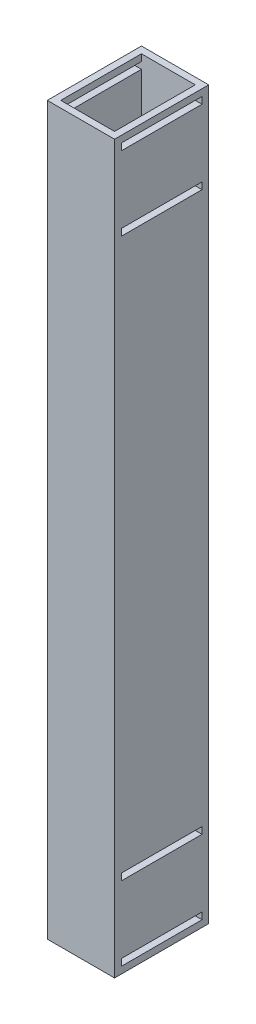
SolidWorks part; units mm, degrees
material "1060 Alloy"
ref_plane "Front Plane" through (0, 0, 0) normal (1, 0, 0) x (0, 1, 0)
ref_plane "Top Plane" through (0, 0, 0) normal (0, 0, 1) x (0, 1, 0)
ref_plane "Right Plane" through (0, 0, 0) normal (0, 1, 0) x (-1, 0, 0)
sketch "Sketch1" plane through (0, 0, 0) normal (0, 1, 0) x (-1, 0, 0)
  line L1 (-25, 35) -> (25, 35)
  line L2 (-25, 35) -> (-25, -35)
  line L3 (-25, -35) -> (25, -35)
  line L4 (25, 35) -> (25, -35)
  line L5 (-25, 35) -> (25, -35) construction
  line L6 (-25, -35) -> (25, 35) construction
  point P0 (0, 0)
  dimension "D1" = 50
  dimension "D2" = 70
extrude "Boss-Extrude1" add sketch "Sketch1" along normal mid plane 540
shell "Shell1" thickness 5
sketch "Sketch2" plane through (25, 0, 0) normal (1, 0, 0) x (0, 1, 0)
  line L0 (-1000, 0) -> (49000, 0) construction
  line L1 (270, 35) -> (-270, 35) construction
  line L2 (-265, 30) -> (-260, 30)
  line L3 (-265, 30) -> (-265, -30)
  line L4 (-265, -30) -> (-260, -30)
  line L5 (-205, 30) -> (-205, -30)
  line L6 (-265, 30) -> (-205, -30) construction
  line L7 (-265, -30) -> (-205, 30) construction
  line L8 (-270, 35) -> (-270, -35) construction
  line L9 (-260, 30) -> (-260, -30)
  line L11 (-210, 30) -> (-210, -30)
  line L13 (-260, 25) -> (-260, -25) construction
  line L14 (-210, 25) -> (-210, -25) construction
  line L15 (-210, 30) -> (-205, 30)
  line L16 (-265, 30) -> (-205, 30) construction
  line L17 (-260, 25) -> (-210, 25) construction
  line L18 (-210, -30) -> (-205, -30)
  line L19 (-265, -30) -> (-205, -30) construction
  line L20 (-260, -25) -> (-210, -25) construction
  line L21 (0, -55) -> (0, 55) construction
  line L22 (265, -30) -> (205, 30) construction
  line L23 (265, 30) -> (205, -30) construction
  line L24 (210, -30) -> (205, -30)
  line L25 (210, 30) -> (205, 30)
  line L26 (210, 30) -> (210, -30)
  line L27 (260, 30) -> (260, -30)
  line L28 (205, 30) -> (205, -30)
  line L29 (265, -30) -> (260, -30)
  line L30 (265, 30) -> (265, -30)
  line L31 (265, 30) -> (260, 30)
  point P1 (-235, 0)
  point P22 (235, 0)
  dimension "D1" = 5
  dimension "D2" = 5
  dimension "D4" = 60
  dimension "D3" = 5
extrude "Cut-Extrude1" cut sketch "Sketch2" against normal through all both and the other way through all
